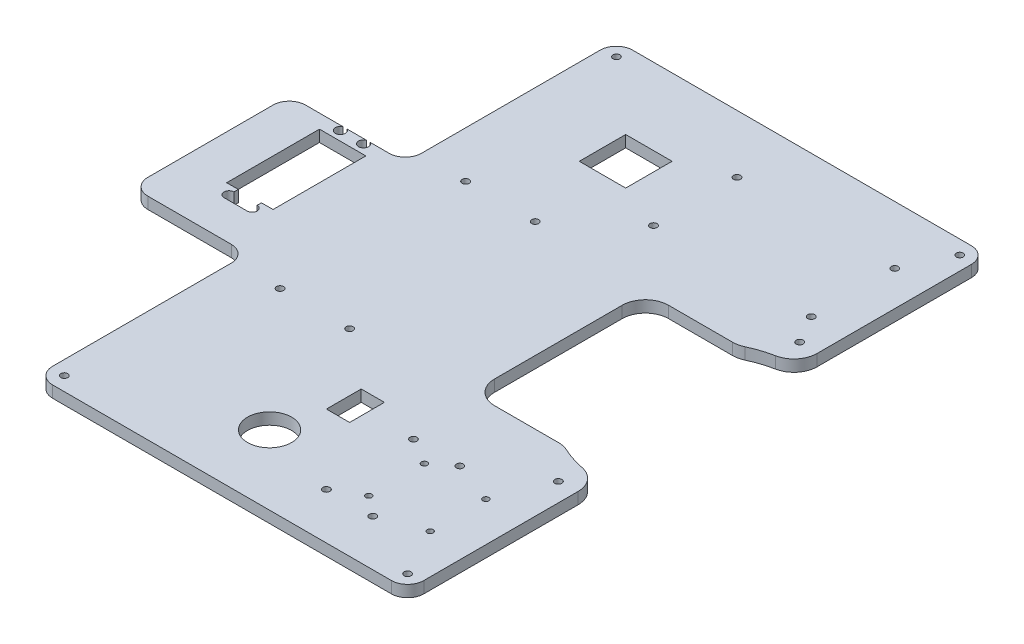
SolidWorks part; units mm, degrees
ref_plane "前视基准面" through (0, 0, 0) normal (0, 0, 1) x (1, 0, 0)
ref_plane "上视基准面" through (0, 0, 0) normal (0, 1, 0) x (1, 0, 0)
ref_plane "右视基准面" through (0, 0, 0) normal (1, 0, 0) x (0, 0, -1)
other "Configuration Table"
sketch "草图1" plane through (0, 0, 0) normal (0, 1, 0) x (1, 0, 0)
  line L0 (80, 0) -> (80, -250) construction
  line L1 (0, 0) -> (160, 0)
  line L2 (0, 0) -> (0, -91)
  line L3 (0, -250) -> (160, -250)
  line L4 (160, 0) -> (160, -82.5)
  line L21 (160, -167.5) -> (160, -250)
  line L22 (-21, -117) -> (-21, -137) construction
  line L27 (0, -91) -> (-50, -91)
  line L32 (160, -81.1586) -> (160, -82.5) construction
  line L33 (-50, -91) -> (-50, -159)
  line L38 (0, -159) -> (-50, -159)
  line L39 (0, -159) -> (0, -250)
  line L50 (77, -25) -> (145, -25) construction
  line L51 (20, -85) -> (50, -85) construction
  line L56 (20, -85) -> (20, -165) construction
  line L57 (20, -165) -> (50, -165) construction
  line L76 (50, -85) -> (50, -165) construction
  line L77 (20, -85) -> (50, -165) construction
  line L88 (80, -125) -> (142.5834, -125) construction
  line L101 (20, -165) -> (50, -85) construction
  line L106 (80, -18.1065) -> (80, -54.1172) construction
  line L109 (100, -87.5) -> (140, -87.5)
  line L110 (100, -87.5) -> (100, -162.5)
  line L111 (100, -162.5) -> (140, -162.5)
  line L113 (100, -87.5) -> (102, -125) construction
  line L114 (100, -162.5) -> (102, -125) construction
  line L119 (77, -25) -> (77, -61) construction
  line L120 (77, -61) -> (145, -61) construction
  line L121 (145, -25) -> (145, -61) construction
  line L122 (77, -25) -> (145, -61) construction
  line L123 (77, -61) -> (145, -25) construction
  line L133 (127, -211.25) -> (145, -211.25) construction
  line L144 (100, -187.5) -> (145, -187.5) construction
  line L145 (100, -187.5) -> (100, -235) construction
  line L146 (100, -235) -> (145, -235) construction
  line L147 (145, -187.5) -> (145, -235) construction
  line L148 (109, -197.25) -> (145, -197.25) construction
  line L149 (109, -197.25) -> (109, -225.25) construction
  line L150 (109, -225.25) -> (145, -225.25) construction
  line L151 (145, -197.25) -> (145, -225.25) construction
  line L152 (109, -197.25) -> (145, -225.25) construction
  line L153 (109, -225.25) -> (145, -197.25) construction
  line L170 (-31, -97) -> (-11, -97)
  line L171 (-31, -97) -> (-31, -137)
  line L175 (35, -165) -> (7, -165) construction
  line L178 (-31, -137) -> (-26, -137)
  line L179 (5.1, -125) -> (80, -125) construction
  line L185 (-11, -97) -> (-11, -137)
  line L186 (-31, -97) -> (-11, -137) construction
  line L187 (-31, -137) -> (-11, -97) construction
  line L188 (-31, -117) -> (-21, -117) construction
  line L189 (-26, -137) -> (-26, -138.85)
  line L190 (-26, -143.15) -> (-16, -143.15)
  line L191 (-16, -138.85) -> (-16, -137)
  line L192 (-16, -137) -> (-11, -137)
  line L193 (81.5884, -43) -> (0, -43) construction
  line L195 (37, -33) -> (57, -33)
  line L196 (37, -33) -> (37, -53)
  line L197 (37, -53) -> (57, -53)
  line L198 (57, -33) -> (57, -53)
  line L199 (37, -33) -> (57, -53) construction
  line L200 (37, -53) -> (57, -33) construction
  line L201 (75, -185) -> (85, -185)
  line L202 (75, -185) -> (75, -200)
  line L203 (75, -200) -> (85, -200)
  line L204 (85, -185) -> (85, -200)
  line L205 (75, -185) -> (85, -200) construction
  line L206 (75, -200) -> (85, -185) construction
  circle A11 centre (154, -6) radius 1.5
  circle A13 centre (6, -6) radius 1.5
  circle A18 centre (6, -244) radius 1.5
  circle A71 centre (80, -8) radius 1.5 construction
  circle A78 centre (154, -244) radius 1.5
  circle A79 centre (152, -73) radius 1.5
  circle A80 centre (80, -242) radius 1.5 construction
  circle A81 centre (152, -177) radius 1.5
  circle A82 centre (8, -76) radius 1.5 construction
  circle A83 centre (8, -172) radius 1.5 construction
  circle A84 centre (20, -85) radius 1.5
  circle A95 centre (77, -25) radius 1.5
  circle A96 centre (145, -25) radius 1.5
  circle A97 centre (145, -61) radius 1.5
  circle A98 centre (77, -61) radius 1.5
  circle A108 centre (143, -223.25) radius 1.3
  circle A109 centre (116.5, -223.25) radius 1.3
  circle A110 centre (143, -199.25) radius 1.3
  circle A111 centre (116.5, -199.25) radius 1.3
  circle A112 centre (105, -230) radius 1.5
  circle A113 centre (125, -230) radius 1.5
  circle A114 centre (105, -192.5) radius 1.5
  circle A115 centre (125, -192.5) radius 1.5
  arc A120 (160, -82.5) -> (140, -87.5) centre (160, -125) ccw
  circle A121 centre (50, -85) radius 1.5
  circle A122 centre (50, -165) radius 1.5
  circle A123 centre (20, -165) radius 1.5
  circle A134 centre (70.5, -220) radius 9.5
  arc A135 (140, -162.5) -> (160, -167.5) centre (160, -125) ccw
  arc A136 (-16, -143.15) -> (-16, -138.85) centre (-16, -141) ccw
  arc A137 (-26, -143.15) -> (-26, -138.85) centre (-26, -141) cw
  circle A138 centre (-16, -93) radius 2.15
  circle A139 centre (-26, -93) radius 2.15
  point P11 (-21, -117)
  point P26 (80, -210)
  point P29 (102, -125)
  point P44 (-50, -125)
  point P54 (35, -125)
  point P60 (81.5884, -43)
  point P96 (47, -43)
  point P103 (145, -43)
  point P104 (80, -192.5)
  point P105 (100, -125)
  point P112 (127, -211.25)
  dimension "D3" = 3
  dimension "D8" = 6
  dimension "D14" = 11
  dimension "D16" = 50
  dimension "D18" = 8
  dimension "D26" = 4
  dimension "D27" = 3
  dimension "D29" = 28
  dimension "D30" = 68
  dimension "D31" = 75
  dimension "D41" = 15
  dimension "D48" = 50
  dimension "D47" = 15
  dimension "D53" = 45
  dimension "D10" = 40
  dimension "D45" = 85
  dimension "D55" = 15
  dimension "D56" = 15
  dimension "D57" = 28
  dimension "D59" = 2
  dimension "D60" = 2
  dimension "D62" = 26.5
  dimension "D64" = 5
  dimension "D65" = 5
  dimension "D66" = 3
  dimension "D17" = 73
  dimension "D19" = 3
  dimension "D21" = 70
  dimension "D23" = 3
  dimension "D33" = 25
  dimension "D36" = 6
  dimension "D38" = 20
  dimension "D34" = 3
  dimension "D42" = 20
  dimension "D44" = 30
  dimension "D61" = 2.6
  dimension "D63" = 2.6
  dimension "D67" = 3
  dimension "D11" = 20
  dimension "D28" = 4.3
  dimension "D43" = 19
  dimension "D1" = 160
  dimension "D2" = 250
  dimension "D6" = 6
  dimension "D7" = 2
  dimension "D9" = 2
  dimension "D12" = 6
  dimension "D13" = 6
  dimension "D15" = 34
  dimension "D20" = 8
  dimension "D22" = 8
  dimension "D24" = 80
  dimension "D25" = 70
  dimension "D32" = 36
  dimension "D35" = 40
  dimension "D37" = 20
  dimension "D39" = 2
  dimension "D40" = 2
  dimension "D46" = 10
  dimension "D54" = 47.5
  dimension "D58" = 36
  dimension "30" = 30
  dimension "D68" = 20
  dimension "D69" = 5
extrude "凸台-拉伸1" add sketch "草图1" along normal blind 5
fillet "圆角1" radius 7 8 edges at (0, 2.5, 0) (160, 2.5, 0) (160, 2.5, 250) (0, 2.5, 250) (0, 2.5, 159) (-50, 2.5, 159) (0, 2.5, 91) (-50, 2.5, 91)
fillet "圆角2" radius 10 6 edges at (160, 2.5, 167.5) (140, 2.5, 162.5) (160, 2.5, 82.5) (140, 2.5, 87.5) (100, 2.5, 162.5) (100, 2.5, 87.5)
